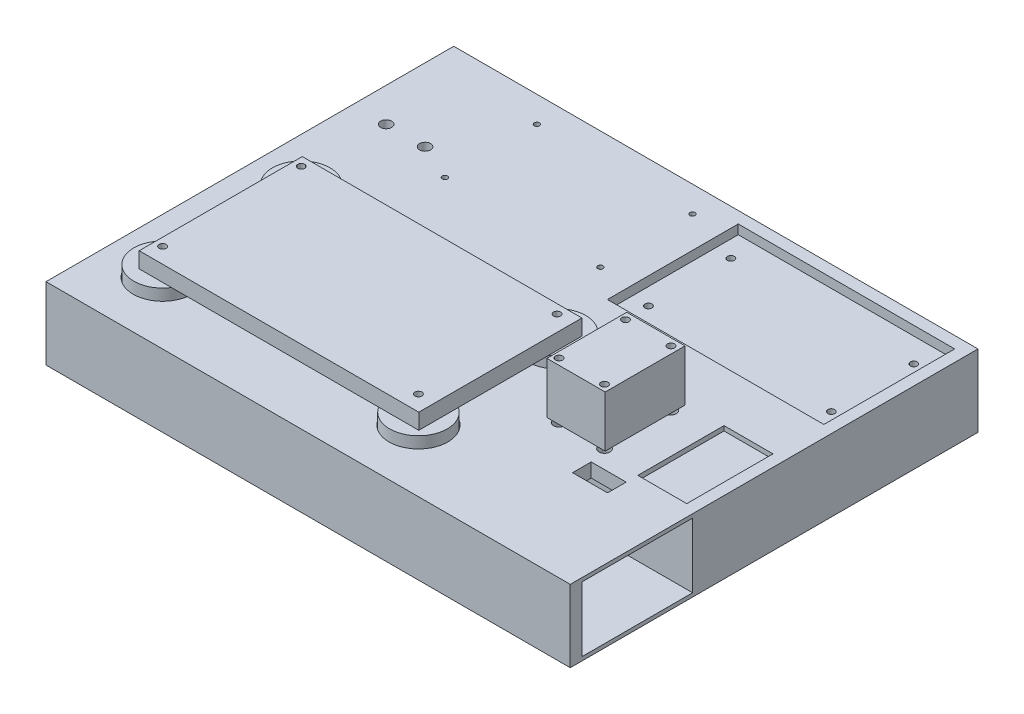
SolidWorks part; units mm, degrees
ref_plane "Front Plane" through (0, 0, 0) normal (0, 0, 1) x (1, 0, 0)
ref_plane "Top Plane" through (0, 0, 0) normal (0, 1, 0) x (1, 0, 0)
ref_plane "Right Plane" through (0, 0, 0) normal (1, 0, 0) x (0, 0, -1)
sketch "Sketch1" plane through (0, 0, 0) normal (0, 1, 0) x (1, 0, 0)
  line L1 (-60, 35) -> (60, 35)
  line L2 (-60, 35) -> (-60, -35)
  line L3 (-60, -35) -> (60, -35)
  line L4 (60, 35) -> (60, -35)
  line L5 (-60, 35) -> (60, -35) construction
  line L6 (-60, -35) -> (60, 35) construction
  circle A0 centre (-56.6, 31.15) radius 1.5
  circle A1 centre (53.2, 31.15) radius 1.5
  circle A2 centre (53.2, -28.35) radius 1.5
  circle A3 centre (-56.6, -28.35) radius 1.5
  point P0 (0, 0)
  point P8 (-55.8832, 32.5985)
  point P9 (0, 0)
  point P10 (0, 0)
  point P13 (0, 0)
  dimension "D3" = 3
  dimension "D1" = 70
  dimension "D2" = 120
  dimension "D4" = 3.85
  dimension "D5" = 3.4
  dimension "D6" = 109.8
  dimension "D7" = 59.5
extrude "Boss-Extrude1" add sketch "Sketch1" along normal blind 6.75
sketch "Sketch3" plane through (0, 0, 0) normal (0, -1, 0) x (1, 0, 0)
  circle A0 centre (-56.6, 28.35) radius 12.375
  circle A1 centre (53.2, 28.35) radius 12.375
  circle A2 centre (53.2, -31.15) radius 12.375
  circle A3 centre (-56.6, -31.15) radius 12.375
  dimension "D1" = 24.75
extrude "Boss-Extrude2" add sketch "Sketch3" along normal offset from surface (9.75 mm away) 16.5 up to face at (53.2, 6.75, 29.85)
sketch "Sketch5" plane through (0, -9.75, 0) normal (0, -1, 0) x (1, 0, 0)
  line L1 (145, 55) -> (-80, 55)
  line L2 (145, 55) -> (145, -120)
  line L3 (145, -120) -> (-80, -120)
  line L4 (-80, 55) -> (-80, -120)
  line L6 (-46.1636, 35) -> (42.7636, 35) construction
  line L7 (-60, -19.2512) -> (-60, 16.4512) construction
  point P6 (2.3891, 57.4934)
  dimension "D1" = 225
  dimension "D2" = 175
  dimension "D3" = 20
  dimension "D4" = 20
extrude "Boss-Extrude3" add sketch "Sketch5" against normal blind 5 and the other way blind 26 separate body
sketch "Sketch8" plane through (0, -4.75, 0) normal (0, 1, 0) x (1, 0, 0)
  circle A3 centre (53.2, 31.15) radius 12.625
  circle A5 centre (-56.6, 31.15) radius 12.625
  circle A6 centre (-56.6, 31.15) radius 12.625
  circle A9 centre (-56.6, -28.35) radius 12.625
  circle A12 centre (53.2, -28.35) radius 12.625
  dimension "D2" = 0.25
extrude "Cut-Extrude3" cut sketch "Sketch8" against normal blind 4
sketch "Sketch9" plane through (0, -4.75, 0) normal (0, 1, 0) x (1, 0, 0)
  line L1 (80, 34.25) -> (105, 34.25)
  line L2 (80, 34.25) -> (80, 0)
  line L3 (80, 0) -> (105, 0)
  line L4 (105, 34.25) -> (105, 0)
  line L6 (60, -35) -> (60, 35) construction
  line L7 (-60, -35) -> (60, -35) construction
  circle A0 centre (101.975, 2.725) radius 1.525
  circle A1 centre (82.475, 2.725) radius 1.525
  circle A2 centre (82.475, 31.225) radius 1.525
  circle A3 centre (101.975, 31.225) radius 1.525
  point P17 (0, 0)
  point P18 (0, 0)
  point P19 (0, 0)
  dimension "D4" = 3.05
  dimension "D7" = 1.5
  dimension "D1" = 25
  dimension "D2" = 34.25
  dimension "D3" = 20
  dimension "D5" = 28.5
  dimension "D6" = 19.5
  dimension "D8" = 1.5
  dimension "D9" = 35
extrude "Boss-Extrude4" add sketch "Sketch9" along normal blind 22 from offset 2 separate body
sketch "Sketch10" plane through (0, -4.75, 0) normal (0, 1, 0) x (1, 0, 0)
  circle A4 centre (101.975, 31.225) radius 2.375
  circle A5 centre (82.475, 31.225) radius 1.525 construction
  circle A6 centre (82.475, 31.225) radius 2.375
  circle A7 centre (101.975, 2.725) radius 2.375
  circle A8 centre (82.475, 2.725) radius 2.375
  circle A13 centre (82.475, 31.225) radius 1.525 construction
  dimension "D1" = 4.75
extrude "Cut-Extrude11" cut sketch "Sketch10" against normal blind 10
sketch "Sketch12" plane through (0, -4.75, 0) normal (0, 1, 0) x (1, 0, 0)
  line L1 (119, 37) -> (140, 37)
  line L2 (119, 37) -> (119, 0)
  line L3 (119, 0) -> (140, 0)
  line L4 (140, 37) -> (140, 0)
  line L9 (145, 120) -> (145, -55) construction
  line L10 (80, 0) -> (105, 0) construction
  dimension "D1" = 37
  dimension "D2" = 21
  dimension "D4" = 5
extrude "Cut-Extrude4" cut sketch "Sketch12" against normal blind 2
sketch "Sketch11" plane through (0, -4.75, 0) normal (0, 1, 0) x (1, 0, 0)
  line L0 (140, 115) -> (47.1, 115)
  line L1 (138, 60.85) -> (49.1, 60.85) construction
  line L2 (138, 60.85) -> (138, 113) construction
  line L3 (138, 113) -> (49.1, 113) construction
  line L4 (49.1, 60.85) -> (49.1, 113) construction
  line L5 (145, 120) -> (145, -55) construction
  line L6 (-80, 120) -> (145, 120) construction
  line L7 (47.1, 58.85) -> (47.1, 115)
  line L8 (140, 58.85) -> (47.1, 58.85)
  line L9 (140, 58.85) -> (140, 115)
  dimension "D1" = 52.15
  dimension "D2" = 88.9
  dimension "D3" = 7
  dimension "D4" = 7
  dimension "D5" = 2
extrude "Cut-Extrude8" cut sketch "Sketch11" against normal blind 4
sketch "Sketch18" plane through (0, -8.75, 0) normal (0, 1, 0) x (1, 0, 0)
  line L0 (138, 113) -> (49.1, 113) construction
  line L1 (49.1, 60.85) -> (49.1, 113) construction
  line L2 (54.3, 104.625) -> (132.8, 104.625) construction
  line L3 (54.3, 69.225) -> (54.3, 104.625) construction
  circle A4 centre (54.3, 104.625) radius 1.5
  circle A5 centre (54.3, 69.225) radius 1.5
  circle A6 centre (132.8, 69.225) radius 1.5
  circle A7 centre (132.8, 104.625) radius 1.5
  dimension "D6" = 3
  dimension "D2" = 8.375
  dimension "D3" = 5.2
  dimension "D4" = 35.4
  dimension "D5" = 78.5
extrude "Cut-Extrude12" cut sketch "Sketch18" against normal blind 10
sketch "Sketch19" plane through (0, -4.75, 0) normal (0, 1, 0) x (1, 0, 0)
  line L9 (-80, 120) -> (145, 120) construction
  line L11 (47.1, 58.85) -> (47.1, 115) construction
  circle A4 centre (33.6, 69.35) radius 1.125
  circle A5 centre (-33.15, 69.35) radius 1.125
  circle A6 centre (-33.15, 108.85) radius 1.125
  circle A7 centre (33.6, 108.85) radius 1.125
  point P5 (47.1, 108.7084)
  dimension "D8" = 2.25
  dimension "D1" = 11.15
  dimension "D2" = 13.5
  dimension "D6" = 66.75
  dimension "D7" = 39.5
extrude "Cut-Extrude13" cut sketch "Sketch19" against normal blind 10
sketch "Sketch20" plane through (0, -4.75, 0) normal (0, 1, 0) x (1, 0, 0)
  line L1 (-70, 93.05) -> (-43.8, 93.05) construction
  line L2 (-70, 93.05) -> (-70, 73.85) construction
  line L3 (-70, 73.85) -> (-43.8, 73.85) construction
  line L4 (-43.8, 93.05) -> (-43.8, 73.85) construction
  line L5 (-33.15, 83.45) -> (-77.9167, 83.45) construction
  circle A0 centre (-65.5, 76.5) radius 1.5 construction
  circle A1 centre (-48.8, 76.5) radius 1.5 construction
  circle A4 centre (-48.8, 76.5) radius 2.375
  circle A5 centre (-65.5, 76.5) radius 2.375
  circle A6 centre (-33.15, 69.35) radius 1.125 construction
  circle A7 centre (-33.15, 69.35) radius 1.125 construction
  dimension "D3" = 3
  dimension "D5" = 3.5
  dimension "D10" = 4.75
  dimension "D1" = 19.2
  dimension "D2" = 26.2
  dimension "D4" = 16.7
  dimension "D6" = 1.15
  dimension "D7" = 4.5
extrude "Cut-Extrude15" cut sketch "Sketch20" against normal blind 10
sketch "Sketch22" plane through (145, 0, 0) normal (-1, 0, 0) x (0, 0, 1)
  line L0 (-120, -35.75) -> (-120, -4.75) construction
  line L1 (2.5, -6.3625) -> (50, -6.3625)
  line L2 (2.5, -6.3625) -> (2.5, -34.1375)
  line L3 (2.5, -34.1375) -> (50, -34.1375)
  line L4 (50, -6.3625) -> (50, -34.1375)
  line L5 (-120, -4.75) -> (-120, -35.75) construction
  line L6 (55, -35.75) -> (-120, -35.75) construction
  line L7 (-120, -20.25) -> (-109.2222, -20.25) construction
  line L8 (55, -35.75) -> (55, -4.75) construction
  point P13 (2.5, -20.25)
  dimension "D1" = 27.775
  dimension "D2" = 47.5
  dimension "D3" = 5
extrude "Cut-Extrude16" cut sketch "Sketch22" along normal blind 20
sketch "Sketch23" plane through (0, -4.75, 0) normal (0, 1, 0) x (1, 0, 0)
  line L1 (119, -5) -> (104, -5)
  line L2 (119, -5) -> (119, -13)
  line L3 (119, -13) -> (104, -13)
  line L4 (104, -5) -> (104, -13)
  line L6 (119, 0) -> (140, 0) construction
  line L7 (119, 37) -> (119, 0) construction
  dimension "D1" = 8
  dimension "D2" = 15
  dimension "D3" = 5
extrude "Cut-Extrude17" cut sketch "Sketch23" against normal up to surface (29.3875 mm away) up to face at (135, -34.1375, 26.25)
sketch "Sketch24" plane through (125, 0, 0) normal (1, 0, 0) x (0, 0, -1)
  line L0 (37, -6.75) -> (-5, -6.75) construction
  line L1 (-50, -34.1375) -> (-2.5, -34.1375)
  line L2 (-50, -34.1375) -> (-50, -10.75)
  line L3 (-50, -10.75) -> (-2.5, -10.75)
  line L4 (-2.5, -34.1375) -> (-2.5, -10.75)
  line L6 (-50, -34.1375) -> (-50, -6.3625) construction
  line L7 (-2.5, -6.3625) -> (-2.5, -34.1375) construction
  dimension "D1" = 4
extrude "Cut-Extrude18" cut sketch "Sketch24" against normal blind 30 contours L2 L1 L4 L3
